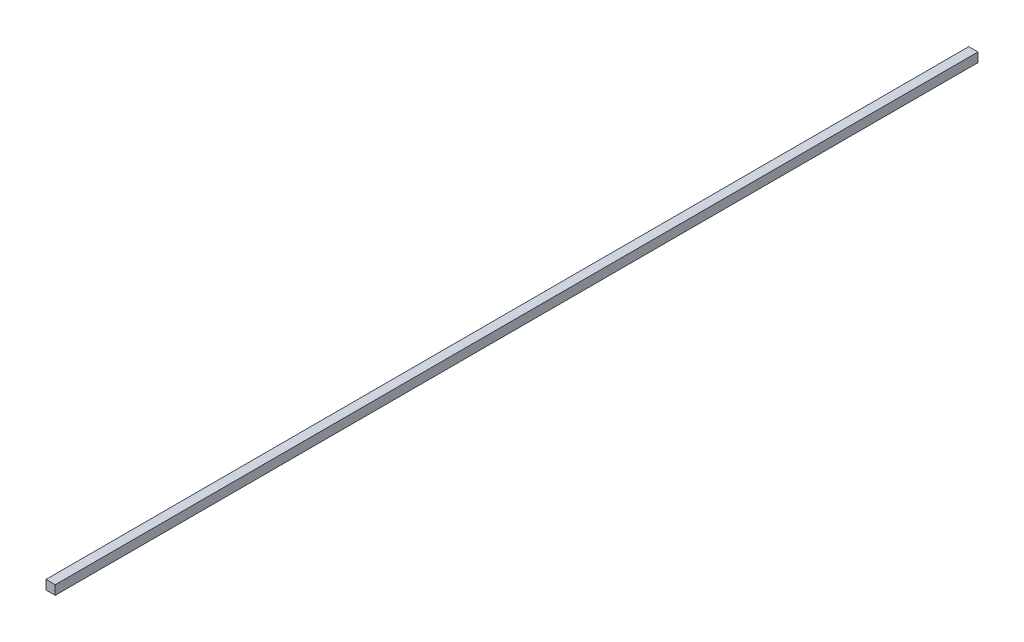
SolidWorks part; units mm, degrees
ref_plane "Front Plane" through (0, 0, 0) normal (0, 0, 1) x (1, 0, 0)
ref_plane "Top Plane" through (0, 0, 0) normal (0, 1, 0) x (1, 0, 0)
ref_plane "Right Plane" through (0, 0, 0) normal (1, 0, 0) x (0, 0, -1)
sketch "Sketch1" plane through (0, 0, 0) normal (0, 0, 1) x (1, 0, 0)
  line L1 (-10, -10) -> (10, -10)
  line L2 (-10, -10) -> (-10, 10)
  line L3 (-10, 10) -> (10, 10)
  line L4 (10, -10) -> (10, 10)
  line L5 (-10, -10) -> (10, 10) construction
  line L6 (-10, 10) -> (10, -10) construction
  point P0 (0, 0)
  dimension "D1" = 20
extrude "Boss-Extrude1" add sketch "Sketch1" along normal blind 2000
